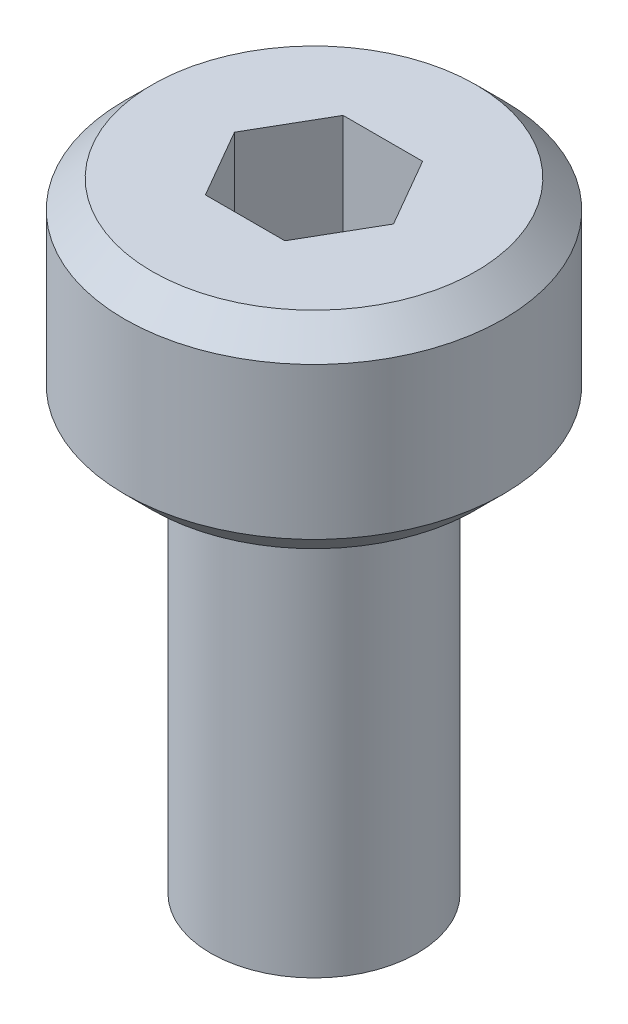
SolidWorks part; units mm, degrees
ref_plane "Front Plane" through (0, 0, 0) normal (0, 0, 1) x (1, 0, 0)
ref_plane "Top Plane" through (0, 0, 0) normal (0, 1, 0) x (1, 0, 0)
ref_plane "Right Plane" through (0, 0, 0) normal (1, 0, 0) x (0, 0, -1)
sketch "Sketch1" plane through (0, 0, 0) normal (0, 0, 1) x (1, 0, 0)
  line L0 (0, 0) -> (0, 9) construction
  line L1 (0, 9) -> (2.75, 9)
  line L2 (2.75, 9) -> (2.75, 6)
  line L3 (2.75, 6) -> (1.5, 6)
  line L4 (1.5, 6) -> (1.5, 0)
  line L5 (1.5, 0) -> (0, 0)
  line L6 (0, 0) -> (0, 9)
  dimension "D1" = 3
  dimension "D2" = 3
  dimension "D3" = 5.5
  dimension "D4" = 9
revolve "Revolve3" add sketch "Sketch1" angle 360 about L0
chamfer "Chamfer1" distance 0.4 angle 45 2 edges at (0, 6, -2.75) (0, 9, -2.75)
sketch "Sketch2" plane through (0, 9, 0) normal (0, 1, 0) x (1, 0, 0)
  line L1 (0.5774, -1) -> (1.1547, 0)
  line L2 (1.1547, 0) -> (0.5774, 1)
  line L3 (0.5774, 1) -> (-0.5774, 1)
  line L4 (-0.5774, 1) -> (-1.1547, 0)
  line L5 (-1.1547, 0) -> (-0.5774, -1)
  line L6 (-0.5774, -1) -> (0.5774, -1)
  circle A0 centre (0, 0) radius 1 construction
  dimension "D1" = 2
extrude "Cut-Extrude1" cut sketch "Sketch2" against normal blind 4
